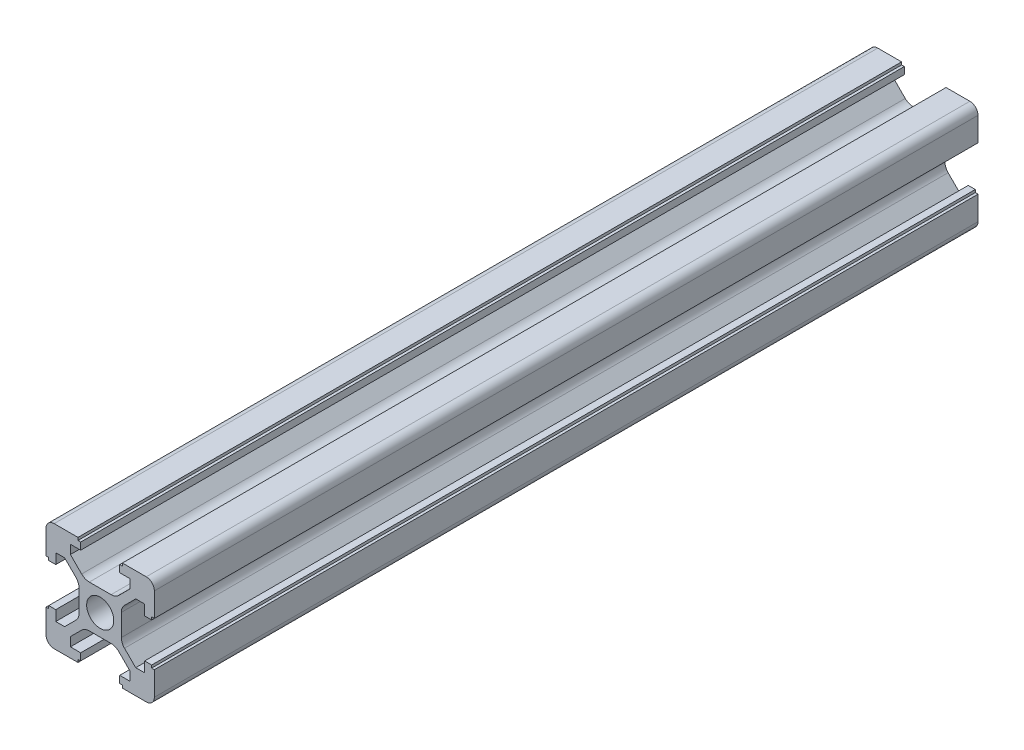
SolidWorks part; units mm, degrees
ref_plane "Front Plane" through (0, 0, 0) normal (0, 0, 1) x (1, 0, 0)
ref_plane "Top Plane" through (0, 0, 0) normal (0, 1, 0) x (1, 0, 0)
ref_plane "Right Plane" through (0, 0, 0) normal (1, 0, 0) x (0, 0, -1)
sketch "Sketch1" plane through (0, 0, 0) normal (0, 0, 1) x (1, 0, 0)
  line L0 (10, -4.1) -> (10, -8.5)
  line L1 (4.1, 10) -> (8.5, 10)
  line L2 (8.5, -10) -> (4.1, -10)
  line L3 (-8.5, -10) -> (-4.1, -10)
  line L4 (10, 8.5) -> (10, 4.1)
  line L7 (8.5, 10) -> (4.1, 10)
  line L8 (5.5, 6.5607) -> (3.4251, 4.4858)
  line L9 (8.5, 10) -> (4.1, 10)
  line L10 (3.9, 2.0109) -> (3.9, -2.0109)
  line L11 (2.0109, -3.9) -> (-2.0109, -3.9)
  line L12 (-3.9, -2.0109) -> (-3.9, 2.0109)
  line L13 (-2.0109, 3.9) -> (2.8393, 3.9)
  line L14 (2.5, 0) -> (22.2403, 0) construction
  line L15 (3.6, 9.5) -> (3.6, 8.2)
  line L16 (9.5, 3.6) -> (8.2, 3.6)
  line L17 (8.2, 3.6) -> (8.2, 5.5)
  line L18 (8.2, 5.5) -> (6.5607, 5.5)
  line L19 (10, -4.1) -> (10, -8.5)
  line L20 (4.1, 9.5) -> (3.6, 9.5)
  line L21 (4.1, 10) -> (4.1, 9.5)
  line L22 (8.5, 10) -> (4.1, 10)
  line L23 (10, 4.1) -> (9.5, 4.1)
  line L24 (9.5, 4.1) -> (9.5, 3.6)
  line L25 (5.5, 8.2) -> (5.5, 6.5607)
  line L26 (3.6, 8.2) -> (5.5, 8.2)
  line L27 (4.4858, 3.4251) -> (6.5607, 5.5)
  line L28 (10, -8.5) -> (10, -4.1)
  line L29 (6.5607, -5.5) -> (4.4858, -3.4251)
  line L30 (10, -8.5) -> (10, -4.1)
  line L31 (2.0109, -3.9) -> (-2.0109, -3.9)
  line L32 (3.9, 2.8393) -> (3.9, -2.0109)
  line L33 (9.5, -3.6) -> (8.2, -3.6)
  line L34 (3.6, -9.5) -> (3.6, -8.2)
  line L35 (3.6, -8.2) -> (5.5, -8.2)
  line L36 (5.5, -8.2) -> (5.5, -6.5607)
  line L37 (9.5, -4.1) -> (9.5, -3.6)
  line L38 (10, -4.1) -> (9.5, -4.1)
  line L39 (10, -8.5) -> (10, -4.1)
  line L40 (4.1, -10) -> (4.1, -9.5)
  line L41 (4.1, -9.5) -> (3.6, -9.5)
  line L42 (8.2, -5.5) -> (6.5607, -5.5)
  line L43 (8.2, -3.6) -> (8.2, -5.5)
  line L44 (3.4251, -4.4858) -> (5.5, -6.5607)
  line L45 (-4.1, -10) -> (-8.5, -10)
  line L46 (-10, -8.5) -> (-10, -4.1)
  line L47 (-8.5, -10) -> (-4.1, -10)
  line L48 (-5.5, -6.5607) -> (-3.4251, -4.4858)
  line L49 (-8.5, -10) -> (-4.1, -10)
  line L50 (-3.9, -2.0109) -> (-3.9, 2.0109)
  line L51 (2.0109, -3.9) -> (-2.0109, -3.9)
  line L52 (-3.6, -9.5) -> (-3.6, -8.2)
  line L53 (-9.5, -3.6) -> (-8.2, -3.6)
  line L54 (-8.2, -3.6) -> (-8.2, -5.5)
  line L55 (-8.2, -5.5) -> (-6.5607, -5.5)
  line L56 (-4.1, -9.5) -> (-3.6, -9.5)
  line L57 (-4.1, -10) -> (-4.1, -9.5)
  line L58 (-8.5, -10) -> (-4.1, -10)
  line L59 (-10, -4.1) -> (-9.5, -4.1)
  line L60 (-9.5, -4.1) -> (-9.5, -3.6)
  line L61 (-5.5, -8.2) -> (-5.5, -6.5607)
  line L62 (-3.6, -8.2) -> (-5.5, -8.2)
  line L63 (-4.4858, -3.4251) -> (-6.5607, -5.5)
  line L64 (-10, 4.1) -> (-10, 8.5)
  line L65 (-8.5, 10) -> (-4.1, 10)
  line L66 (-10, 8.5) -> (-10, 4.1)
  line L67 (-6.5607, 5.5) -> (-4.4858, 3.4251)
  line L68 (-10, 8.5) -> (-10, 4.1)
  line L69 (-2.0109, 3.9) -> (2.0109, 3.9)
  line L70 (-3.9, -2.0109) -> (-3.9, 2.0109)
  line L71 (-9.5, 3.6) -> (-8.2, 3.6)
  line L72 (-3.6, 9.5) -> (-3.6, 8.2)
  line L73 (-3.6, 8.2) -> (-5.5, 8.2)
  line L74 (-5.5, 8.2) -> (-5.5, 6.5607)
  line L75 (-9.5, 4.1) -> (-9.5, 3.6)
  line L76 (-10, 4.1) -> (-9.5, 4.1)
  line L77 (-10, 8.5) -> (-10, 4.1)
  line L78 (-4.1, 10) -> (-4.1, 9.5)
  line L79 (-4.1, 9.5) -> (-3.6, 9.5)
  line L80 (-8.2, 5.5) -> (-6.5607, 5.5)
  line L81 (-8.2, 3.6) -> (-8.2, 5.5)
  line L82 (-3.4251, 4.4858) -> (-5.5, 6.5607)
  line L83 (4.1, -10) -> (8.5, -10)
  arc A0 (2.0109, -3.9) -> (3.4251, -4.4858) centre (2.0109, -5.9) cw
  arc A1 (4.4858, -3.4251) -> (3.9, -2.0109) centre (5.9, -2.0109) cw
  arc A2 (3.9, 2.0109) -> (4.4858, 3.4251) centre (5.9, 2.0109) cw
  arc A3 (2.0109, 3.9) -> (3.4251, 4.4858) centre (2.0109, 5.9) ccw
  arc A4 (-2.0109, 3.9) -> (-3.4251, 4.4858) centre (-2.0109, 5.9) cw
  arc A5 (-4.4858, 3.4251) -> (-3.9, 2.0109) centre (-5.9, 2.0109) cw
  arc A6 (-3.4251, -4.4858) -> (-2.0109, -3.9) centre (-2.0109, -5.9) cw
  arc A7 (-3.9, -2.0109) -> (-4.4858, -3.4251) centre (-5.9, -2.0109) cw
  circle A8 centre (0, 0) radius 2.5
  arc A9 (-8.5, -10) -> (-10, -8.5) centre (-8.5, -8.5) cw
  arc A10 (-10, 8.5) -> (-8.5, 10) centre (-8.5, 8.5) cw
  arc A11 (8.5, 10) -> (10, 8.5) centre (8.5, 8.5) cw
  arc A12 (8.5, -10) -> (10, -8.5) centre (8.5, -8.5) ccw
  point P0 (0, 0)
  point P86 (0, 0)
  point P107 (10, -10)
  dimension "D3" = 2
  dimension "D5" = 5
  dimension "D2" = 1.5
  dimension "D8" = 1.5
  dimension "D4" = 6.1
  dimension "D6" = 20
  dimension "D7" = 6.1
  dimension "D9" = 20
  dimension "D11" = 0.5
  dimension "D12" = 0.5
extrude "Boss-Extrude2" add sketch "Sketch1" along normal blind 152
